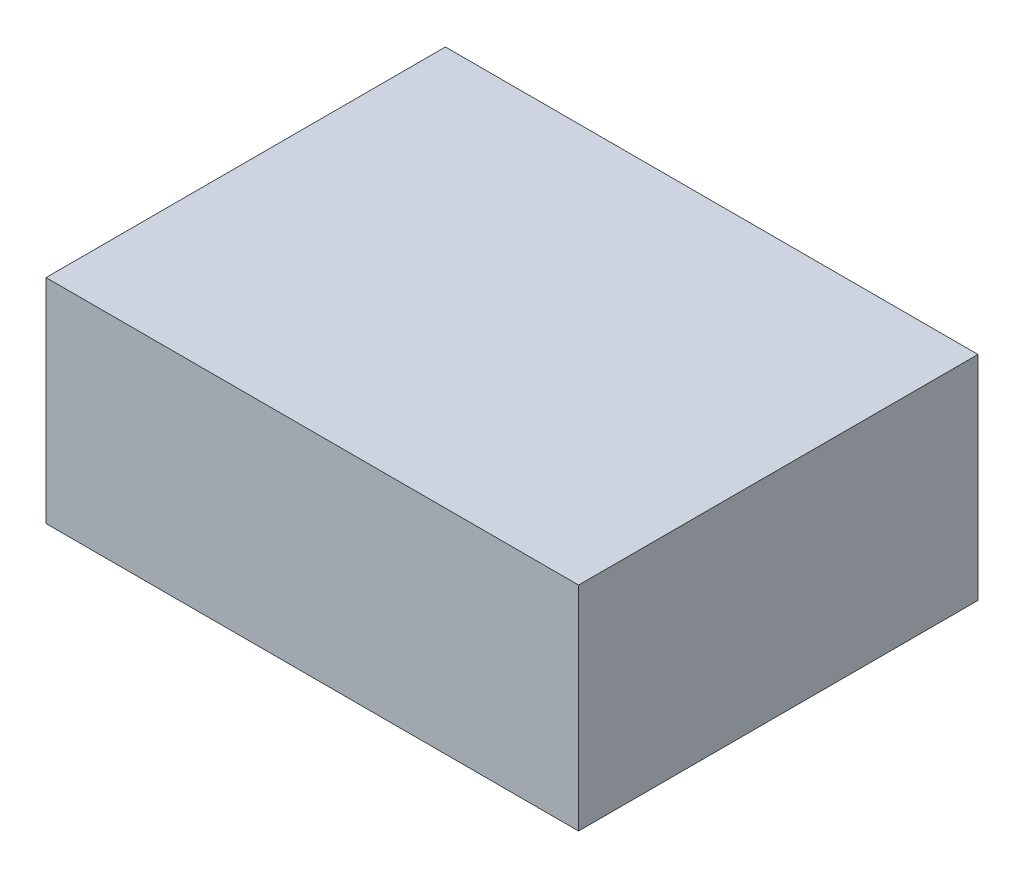
SolidWorks part; units mm, degrees
material "3.0205 (EN-AW 1200)"
ref_plane "Alzado" through (0, 0, 0) normal (0, 0, 1) x (1, 0, 0)
ref_plane "Planta" through (0, 0, 0) normal (0, 1, 0) x (1, 0, 0)
ref_plane "Vista lateral" through (0, 0, 0) normal (1, 0, 0) x (0, 0, -1)
sketch "Croquis1" plane through (0, 0, 0) normal (0, 1, 0) x (1, 0, 0)
  line L1 (-10, 7.5) -> (10, 7.5)
  line L2 (-10, 7.5) -> (-10, -7.5)
  line L3 (-10, -7.5) -> (10, -7.5)
  line L4 (10, 7.5) -> (10, -7.5)
  line L5 (-10, 7.5) -> (10, -7.5) construction
  line L6 (-10, -7.5) -> (10, 7.5) construction
  point P0 (0, 0)
  dimension "D1" = 15
  dimension "D2" = 20
extrude "Saliente-Extruir1" add sketch "Croquis1" against normal blind 8
